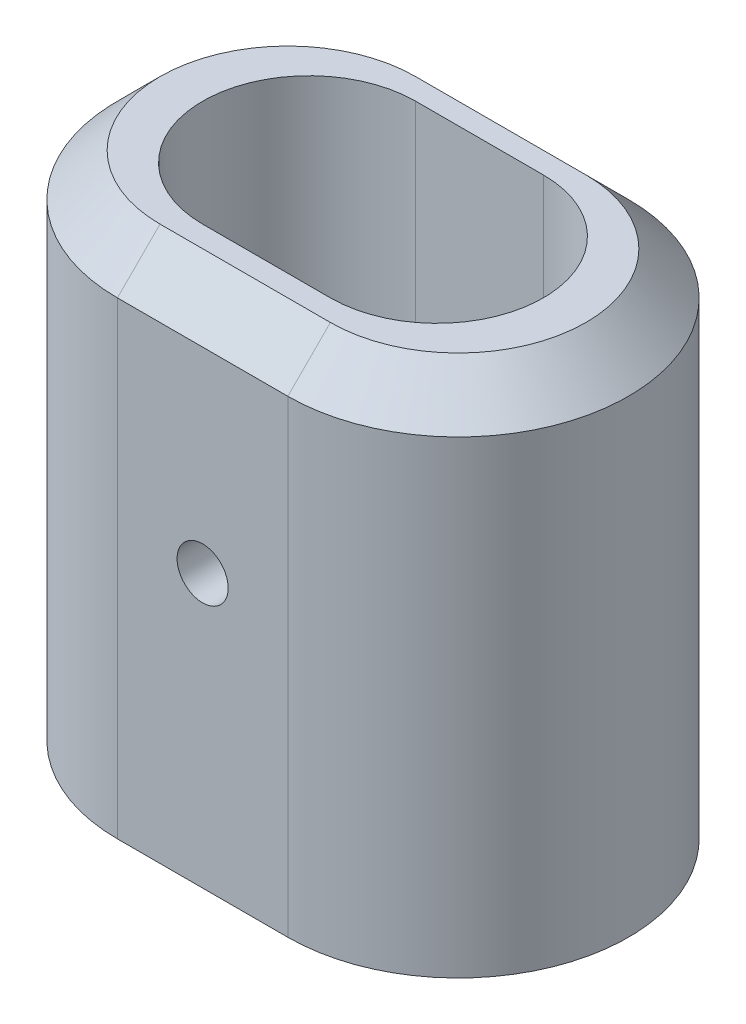
SolidWorks part; units mm, degrees
ref_plane "前基準面" through (0, 0, 0) normal (0, 0, 1) x (1, 0, 0)
ref_plane "上基準面" through (0, 0, 0) normal (0, 1, 0) x (1, 0, 0)
ref_plane "右基準面" through (0, 0, 0) normal (1, 0, 0) x (0, 0, -1)
ref_plane "平面1"
sketch "草圖1" plane through (0, 0, 0) normal (0, 1, 0) x (-1, 0, 0)
  line L0 (10, -20) -> (-10, -20)
  line L1 (-10, 20) -> (10, 20)
  line L2 (7.5, -12.5) -> (-7.5, -12.5)
  line L3 (-7.5, 12.5) -> (7.5, 12.5)
  arc A0 (-10, 20) -> (-10, -20) centre (-10, 0) ccw
  arc A1 (10, -20) -> (10, 20) centre (10, 0) ccw
  arc A2 (-7.5, 12.5) -> (-7.5, -12.5) centre (-7.5, 0) ccw
  arc A3 (7.5, -12.5) -> (7.5, 12.5) centre (7.5, 0) ccw
  dimension "D2" = 20
  dimension "D3" = 20
  dimension "D4" = 12.5
  dimension "D5" = 12.5
  dimension "D1" = 10
  dimension "D6" = 10
extrude "擠出1" add sketch "草圖1" along normal blind 60 contours L0 A1 L1 A0 A3 L2 A2 L3
chamfer "倒角1" distance 5 distance2 5 4 edges at (30, 60, 0) (0, 60, -20) (-30, 60, 0) (0, 60, 20)
sketch "草圖2" plane through (0, 0, 20) normal (0, 0, 1) x (1, 0, 0)
  line L0 (-10, 60) -> (-10, 55) construction
  circle A0 centre (0, 32) radius 3
  dimension "D1" = 6
  dimension "D2" = 10
extrude "擠出2" cut sketch "草圖2" against normal blind 60
